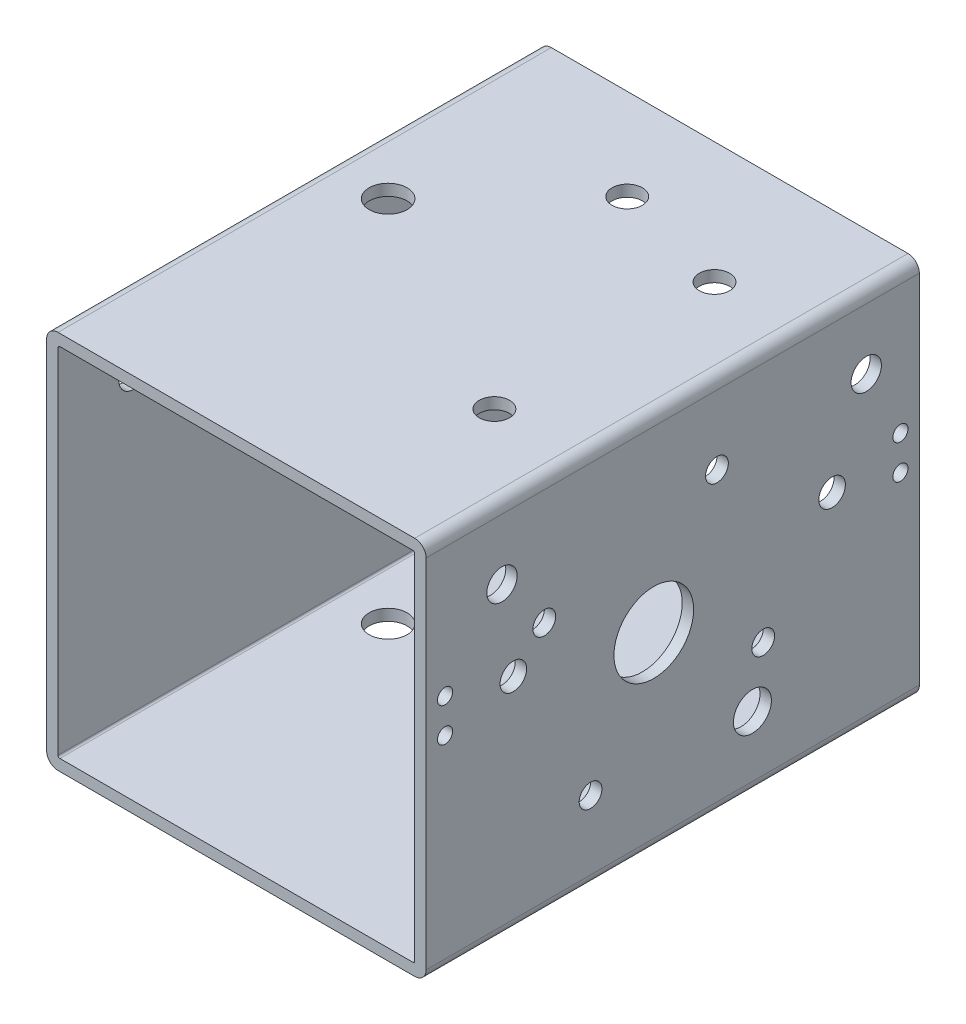
SolidWorks part; units mm, degrees
ref_plane "Front Plane" through (0, 0, 0) normal (0, 0, 1) x (1, 0, 0)
ref_plane "Top Plane" through (0, 0, 0) normal (0, 1, 0) x (1, 0, 0)
ref_plane "Right Plane" through (0, 0, 0) normal (1, 0, 0) x (0, 0, -1)
sketch "Sketch1" plane through (0, 0, 0) normal (0, 0, 1) x (1, 0, 0)
  line L1 (-50, 50) -> (50, 50)
  line L2 (-50, 50) -> (-50, -50)
  line L3 (-50, -50) -> (50, -50)
  line L4 (50, 50) -> (50, -50)
  line L5 (-50, 50) -> (50, -50) construction
  line L6 (-50, -50) -> (50, 50) construction
  point P0 (0, 0)
  dimension "D1" = 100
  dimension "D2" = 100
extrude "Extrude-Thin1" add sketch "Sketch1" along normal blind 130 thin
fillet "Fillet1" radius 0.5 4 edges at (-47, -47, 65) (-47, 47, 65) (47, 47, 65) (47, -47, 65)
fillet "Fillet2" radius 3 4 edges at (50, -50, 65) (-50, -50, 65) (50, 50, 65) (-50, 50, 65)
sketch "Holes - top" plane through (0, 0, 0) normal (0, 1, 0) x (1, 0, 0)
  line L0 (-3, 0) -> (-3, -130) construction
  line L1 (47, -130) -> (-47, -130) construction
  line L2 (-23, 0) -> (-23, -130) construction
  line L3 (47, 0) -> (-47, 0) construction
  line L4 (17, 0) -> (17, -130) construction
  circle A0 centre (-34, -56) radius 11 construction
  circle A1 centre (28, -90) radius 11 construction
  circle A2 centre (28, -32) radius 11 construction
  dimension "D4" = 22
  dimension "D1" = 40
  dimension "D2" = 40
  dimension "D3" = 32
  dimension "D5" = 56
  dimension "D6" = 3
hole_wizard "Ø8.0 (8) Diameter Hole2" positions "Sketch6" profile "Sketch5" hole size "Ø8.0" standard "ANSI Metric" end condition through all
sketch "Sketch6" plane through (0, 50, 0) normal (0, 1, 0) x (1, 0, 0)
  point P0 (28, -32)
  point P6 (28, -90)
sketch "Sketch5" plane through (28, 50, 32) normal (1, 0, 0) x (0, 0, 1)
  line L0 (0, 0) -> (0, 100)
  line L1 (0, 100) -> (4, 100)
  line L2 (4, 100) -> (4, 0)
  line L5 (4, 0) -> (0, 0)
  line L11 (0, -6.35) -> (0, 107.95) construction
  dimension "Thru Hole Dia." = 8
  dimension "Thru Hole Depth" = 100
sketch "Holes - side" plane through (0, 0, 0) normal (1, 0, 0) x (0, 0, -1)
  line L0 (0, 0) -> (-130, 0) construction
  line L1 (-130, -47) -> (-130, 47) construction
  line L2 (-130, 20) -> (0, 20) construction
  line L3 (0, -47) -> (0, 47) construction
  line L4 (-130, -20) -> (0, -20) construction
  circle A0 centre (-110, 31) radius 11 construction
  circle A1 centre (-14, 31) radius 11 construction
  circle A2 centre (-44, -31) radius 11 construction
  dimension "D1" = 40
  dimension "D2" = 22
  dimension "D3" = 20
  dimension "D4" = 14
  dimension "D5" = 44
hole_wizard "Ø8.0 (8) Diameter Hole3" positions "Sketch9" profile "Sketch8" hole size "Ø8.0" standard "ANSI Metric" end condition through all
sketch "Sketch9" plane through (50, 0, 0) normal (1, 0, 0) x (0, 0, -1)
  point P0 (-14, 31)
  point P3 (-110, 31)
sketch "Sketch8" plane through (50, 31, 14) normal (0, 1, 0) x (0, 0, -1)
  line L0 (0, 0) -> (0, 100)
  line L1 (0, 100) -> (4, 100)
  line L2 (4, 100) -> (4, 0)
  line L5 (4, 0) -> (0, 0)
  line L11 (0, -6.35) -> (0, 107.95) construction
  dimension "Thru Hole Dia." = 8
  dimension "Thru Hole Depth" = 100
hole_wizard "Ø10.0 (10) Diameter Hole1" positions "Sketch12" profile "Sketch11" hole size "Ø10.0" standard "ANSI Metric" end condition through all
sketch "Sketch12" plane through (0, 50, 0) normal (0, 1, 0) x (1, 0, 0)
  point P0 (-34, -56)
sketch "Sketch11" plane through (-34, 50, 56) normal (1, 0, 0) x (0, 0, 1)
  line L0 (0, 0) -> (0, 100)
  line L1 (0, 100) -> (5, 100)
  line L2 (5, 100) -> (5, 0)
  line L5 (5, 0) -> (0, 0)
  line L11 (0, -6.35) -> (0, 107.95) construction
  dimension "Thru Hole Dia." = 10
  dimension "Thru Hole Depth" = 100
hole_wizard "Ø10.0 (10) Diameter Hole2" positions "Sketch14" profile "Sketch13" hole size "Ø10.0" standard "ANSI Metric" end condition through all
sketch "Sketch14" plane through (50, 0, 0) normal (1, 0, 0) x (0, 0, -1)
  point P0 (-44, -31)
sketch "Sketch13" plane through (50, -31, 44) normal (0, 1, 0) x (0, 0, -1)
  line L0 (0, 0) -> (0, 100)
  line L1 (0, 100) -> (5, 100)
  line L2 (5, 100) -> (5, 0)
  line L5 (5, 0) -> (0, 0)
  line L11 (0, -6.35) -> (0, 107.95) construction
  dimension "Thru Hole Dia." = 10
  dimension "Thru Hole Depth" = 100
hole_wizard "M8x1.25 Tapped Hole1" positions "Sketch18" profile "Sketch17" tap size "M8x1.25" standard "ANSI Metric"
sketch "Sketch18" plane through (-50, 0, 0) normal (-1, 0, 0) x (0, 0, 1)
  line L0 (56, 35) -> (56, -15) construction
  point P0 (56, -15)
  point P2 (56, 35)
  dimension "D1" = 56
  dimension "D2" = 35
  dimension "D3" = 15
sketch "Sketch17" plane through (-50, -15, 56) normal (0, 1, 0) x (0, 0, 1)
  line L0 (0, 0) -> (0, 3)
  line L1 (0, 3) -> (3.4, 3)
  line L2 (3.4, 3) -> (3.4, 0)
  line L5 (3.4, 0) -> (0, 0)
  line L11 (0, -6.35) -> (0, 107.95) construction
  dimension "Thru Tap Drill Dia." = 6.8
  dimension "Thru Tap Drill Depth" = 3
cosmetic thread "Hole Thread1" parameters "D2"=8
cosmetic thread "Hole Thread2" parameters "D2"=8
hole_wizard "M8x1.25 Tapped Hole2" positions "Sketch21" profile "Sketch20" tap size "M8x1.25" standard "ANSI Metric"
sketch "Sketch21" plane through (0, -50, 0) normal (0, -1, 0) x (-1, 0, 0)
  line L0 (20, -44) -> (-35, -44) construction
  point P0 (20, -44)
  point P2 (-35, -44)
  dimension "D1" = 44
  dimension "D2" = 35
  dimension "D3" = 20
sketch "Sketch20" plane through (-20, -50, 44) normal (1, 0, 0) x (0, 0, -1)
  line L0 (0, 0) -> (0, 3)
  line L1 (0, 3) -> (3.4, 3)
  line L2 (3.4, 3) -> (3.4, 0)
  line L5 (3.4, 0) -> (0, 0)
  line L11 (0, -6.35) -> (0, 107.95) construction
  dimension "Thru Tap Drill Dia." = 6.8
  dimension "Thru Tap Drill Depth" = 3
cosmetic thread "Hole Thread3" parameters "D2"=8
cosmetic thread "Hole Thread4" parameters "D2"=8
sketch "Holes - Nema 23 motor" plane through (0, 0, 0) normal (1, 0, 0) x (0, 0, -1)
  line L0 (-98.8427, 16.6524) -> (-53.3476, 28.8427) construction
  line L1 (-98.8427, 16.6524) -> (-86.6524, -28.8427) construction
  line L2 (-53.3476, 28.8427) -> (-41.1573, -16.6524) construction
  line L3 (-86.6524, -28.8427) -> (-41.1573, -16.6524) construction
  line L4 (-98.8427, 16.6524) -> (-41.1573, -16.6524) construction
  line L5 (-53.3476, 28.8427) -> (-86.6524, -28.8427) construction
  line L6 (0, 0) -> (-130, 0) construction
  point P1 (-70, 0)
  dimension "D1" = 70
  dimension "D2" = 47.1
  dimension "D3" = 47.1
  dimension "D4" = 15
hole_wizard "Ø21.0 (21) Diameter Hole1" positions "Sketch24" profile "Sketch23" hole size "Ø21.0" standard "ANSI Metric"
sketch "Sketch24" plane through (50, 0, 0) normal (1, 0, 0) x (0, 0, -1)
  point P0 (-70, 0)
sketch "Sketch23" plane through (50, 0, 70) normal (0, 1, 0) x (0, 0, -1)
  line L0 (0, 0) -> (0, 3)
  line L1 (0, 3) -> (10.5, 3)
  line L2 (10.5, 3) -> (10.5, 0)
  line L5 (10.5, 0) -> (0, 0)
  line L11 (0, -6.35) -> (0, 107.95) construction
  dimension "Thru Hole Dia." = 21
  dimension "Thru Hole Depth" = 3
hole_wizard "Ø6.0 (6) Diameter Hole1" positions "Sketch26" profile "Sketch25" hole size "Ø6.0" standard "ANSI Metric"
sketch "Sketch26" plane through (50, 0, 0) normal (1, 0, 0) x (0, 0, -1)
  point P0 (-41.1573, -16.6524)
  point P3 (-53.3476, 28.8427)
  point P6 (-98.8427, 16.6524)
  point P9 (-86.6524, -28.8427)
sketch "Sketch25" plane through (50, -16.6524, 41.1573) normal (0, 1, 0) x (0, 0, -1)
  line L0 (0, 0) -> (0, 3)
  line L1 (0, 3) -> (3, 3)
  line L2 (3, 3) -> (3, 0)
  line L5 (3, 0) -> (0, 0)
  line L11 (0, -6.35) -> (0, 107.95) construction
  dimension "Thru Hole Dia." = 6
  dimension "Thru Hole Depth" = 3
hole_wizard "Ø8.0 (8) Diameter Hole4" positions "Sketch29" profile "Sketch28" hole size "Ø8.0" standard "ANSI Metric"
sketch "Sketch29" plane through (0, 50, 0) normal (0, 1, 0) x (1, 0, 0)
  line L0 (-3, 0) -> (-3, -130) construction
  point P0 (-3, -24)
  dimension "D2" = 8
sketch "Sketch28" plane through (-3, 50, 24) normal (1, 0, 0) x (0, 0, 1)
  line L0 (0, 0) -> (0, 3)
  line L1 (0, 3) -> (4, 3)
  line L2 (4, 3) -> (4, 0)
  line L5 (4, 0) -> (0, 0)
  line L11 (0, -6.35) -> (0, 107.95) construction
  dimension "Thru Hole Dia." = 8
  dimension "Thru Hole Depth" = 3
sketch "Sketch31" plane through (50, 0, 0) normal (1, 0, 0) x (0, 0, -1)
  line L0 (0, -47) -> (0, 47) construction
  line L1 (-130, 50) -> (0, 50) construction
  line L2 (-65, 117.0212) -> (-65, -118.5233) construction
  line L3 (-130, -47) -> (-130, 47) construction
  circle A0 centre (-5, 4) radius 2
  circle A1 centre (-5, 13) radius 2
  circle A2 centre (-125, 13) radius 2
  circle A3 centre (-125, 4) radius 2
  circle A4 centre (-23, 8.5) radius 3.5
  circle A5 centre (-107, 8.5) radius 3.5
  dimension "D1" = 4
  dimension "D2" = 4
  dimension "D3" = 9
  dimension "D4" = 5
  dimension "D5" = 46
  dimension "D6" = 5
  dimension "D8" = 7
  dimension "D9" = 18
  dimension "D7" = 65
  dimension "D10" = 4.5
extrude "Cut-Extrude1" cut sketch "Sketch31" against normal up to next
equation "\"a\"= \"Trolley Profile@Plasma Beta.Assembly\""
equation "\"b\"= \"Trolley Profile Thickness@Plasma Beta.Assembly\""
equation "\"L\"= 130"
equation "\"D2@Sketch1\"=\"a\""
equation "\"D1@Sketch1\"=\"a\""
equation "\"D1@Extrude-Thin1\"=\"L\""
equation "\"D5@Extrude-Thin1\"=\"b\""
equation "\"D1@Fillet2\"=\"b\""
equation "\"d-bearing\"= 22'diameter of bearing"
equation "\"a-small\"= \"Beam Profile@Plasma Beta.Assembly\"'profile of smaller beam"
equation "\"D4@Holes - top\"=\"d-bearing\""
equation "\"D2@Holes - side\"=\"d-bearing\""
equation "\"D1@Holes - top\"=\"a-small\""
equation "\"D1@Holes - side\"=\"a-small\""
